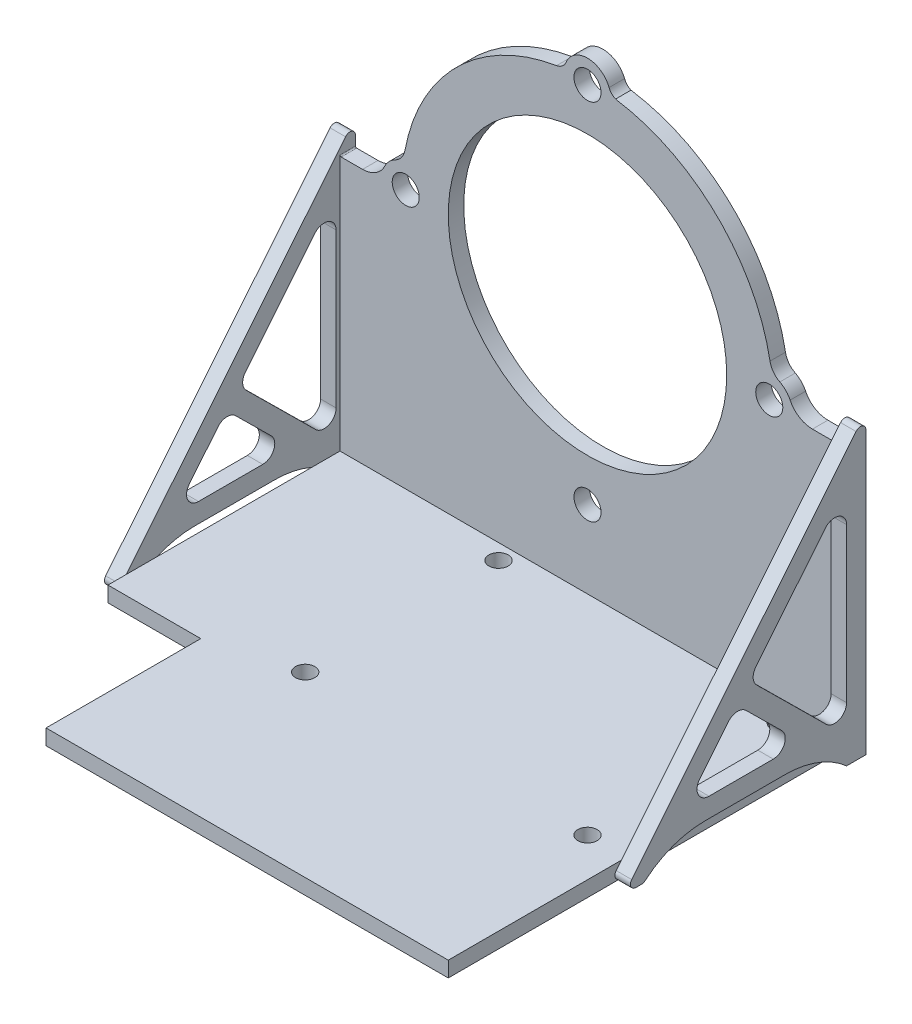
SolidWorks part; units mm, degrees
ref_plane "Front Plane" through (0, 0, 0) normal (0, 0, 1) x (1, 0, 0)
ref_plane "Top Plane" through (0, 0, 0) normal (0, 1, 0) x (1, 0, 0)
ref_plane "Right Plane" through (0, 0, 0) normal (1, 0, 0) x (0, 0, -1)
sketch "Sketch2" plane through (0, 0, 0) normal (0, 1, 0) x (1, 0, 0)
  line L0 (0, 0) -> (0, -101.6)
  line L1 (0, -101.6) -> (38.1, -101.6)
  line L2 (38.1, -101.6) -> (38.1, -165.1)
  line L3 (38.1, -165.1) -> (203.2, -165.1)
  line L4 (203.2, -165.1) -> (203.2, 0)
  line L5 (203.2, 0) -> (0, 0)
  dimension "D1" = 165.1
  dimension "D2" = 165.1
  dimension "D3" = 63.5
  dimension "D4" = 38.1
extrude "Boss-Extrude1" add sketch "Sketch2" along normal blind 6.35
sketch "Sketch3" plane through (0, 0, 0) normal (0, 0, 1) x (1, 0, 0)
  line L0 (203.2, 6.35) -> (203.2, 196.85)
  line L1 (203.2, 196.85) -> (0, 196.85)
  line L2 (0, 196.85) -> (0, 6.35)
  line L3 (0, 6.35) -> (203.2, 6.35)
  dimension "D1" = 190.5
extrude "Boss-Extrude2" add sketch "Sketch3" along normal blind 6.35
sketch "Sketch4" plane through (0, 0, 6.35) normal (0, 0, 1) x (1, 0, 0)
  line L0 (0, 6.35) -> (101.6, 6.35) construction
  line L1 (38.1, 6.35) -> (203.2, 6.35) construction
  line L2 (101.6, 6.35) -> (101.6, 112.7125) construction
  circle A0 centre (101.6, 112.7125) radius 57.15
  dimension "D3" = 114.3
  dimension "D1" = 101.6
  dimension "D2" = 106.3625
extrude "Cut-Extrude1" cut sketch "Sketch4" against normal blind 6.35
sketch "Sketch5" plane through (0, 0, 0) normal (0, 0, -1) x (-1, 0, 0)
  line L0 (0, 6.35) -> (-203.2, 6.35) construction
  line L1 (-101.6, 6.35) -> (-101.6, 38.1) construction
  circle A0 centre (-101.6, 38.1) radius 5.5563
  circle A1 centre (-101.6, 112.7125) radius 74.6125 construction
  circle A2 centre (-101.6, 187.325) radius 5.5563
  circle A3 centre (-26.9875, 112.7125) radius 5.5562
  circle A4 centre (-176.2125, 112.7125) radius 5.5563
  dimension "D2" = 11.1125
  dimension "D1" = 31.75
extrude "Cut-Extrude2" cut sketch "Sketch5" against normal blind 6.35
sketch "Sketch6" plane through (0, 0, 0) normal (0, 0, -1) x (-1, 0, 0)
  line L0 (-44.45, 112.7125) -> (-25.4, 112.7125) construction
  line L1 (0, 0) -> (0, 111.125) construction
  line L2 (0, 196.85) -> (0, 0) construction
  line L3 (0, 111.125) -> (-203.2, 111.125) construction
  line L4 (-203.2, 196.85) -> (-203.2, 0) construction
  line L5 (0, 111.125) -> (-9.2671, 111.125)
  line L6 (-88.3893, 190.8124) -> (-114.449, 190.8124) construction
  line L7 (-7.9098, 126.5898) -> (-186.0002, 126.5898) construction
  line L8 (-20.9502, 121.1931) -> (-193.0529, 121.1931) construction
  line L9 (-203.2, 111.125) -> (-193.9329, 111.125)
  line L10 (-203.2, 111.125) -> (-224.6051, 111.125)
  line L11 (-224.6051, 111.125) -> (-224.6051, 212.9952)
  line L12 (-224.6051, 212.9952) -> (24.4438, 212.9952)
  line L13 (24.4438, 212.9952) -> (24.4438, 111.125)
  line L14 (24.4438, 111.125) -> (0, 111.125)
  circle A0 centre (-101.6, 112.7125) radius 76.2 construction
  circle A1 centre (-101.6, 112.7125) radius 57.15 construction
  circle A2 centre (-101.6, 187.325) radius 9.525 construction
  circle A3 centre (-26.9875, 112.7125) radius 9.525 construction
  circle A4 centre (-176.2125, 112.7125) radius 9.525 construction
  arc A5 (-9.2671, 111.125) -> (-18.4131, 116.8605) centre (-9.2671, 121.285) cw
  arc A6 (-18.4131, 116.8605) -> (-22.651, 121.1931) centre (-26.9875, 112.7125) ccw
  arc A7 (-22.651, 121.1931) -> (-26.6743, 126.5898) centre (-19.1817, 127.9775) cw
  arc A8 (-26.6743, 126.5898) -> (-88.9325, 187.8522) centre (-101.6, 112.7125) ccw
  arc A9 (-88.9325, 187.8522) -> (-92.7364, 190.8124) centre (-88.088, 192.8615) cw
  arc A10 (-92.7364, 190.8124) -> (-110.4636, 190.8124) centre (-101.6, 187.325) ccw
  arc A11 (-110.4636, 190.8124) -> (-113.1099, 188.0382) centre (-115.1908, 192.6724) cw
  arc A12 (-113.1099, 188.0382) -> (-176.5257, 126.5898) centre (-101.6, 112.7125) ccw
  arc A13 (-176.5257, 126.5898) -> (-180.549, 121.1931) centre (-184.0183, 127.9775) cw
  arc A14 (-193.9329, 111.125) -> (-184.7869, 116.8605) centre (-193.9329, 121.285) ccw
  arc A15 (-184.7869, 116.8605) -> (-180.549, 121.1931) centre (-176.2125, 112.7125) cw
  point P49 (0, 0)
  point P53 (0, 0)
  dimension "D1" = 19.05
  dimension "D2" = 19.05
  dimension "D7" = 5.08
  dimension "D8" = 2.6463
  dimension "D10" = 10.16
  dimension "D9" = 7.62
  dimension "D11" = 5.08
  dimension "D12" = 7.62
  dimension "D13" = 10.16
  dimension "D3" = 111.125
  dimension "D5" = 249.0489
  dimension "D6" = 21.4051
extrude "Cut-Extrude3" cut sketch "Sketch6" against normal blind 6.35
sketch "Sketch7" plane through (0, 6.35, 0) normal (0, 1, 0) x (1, 0, 0)
  line L0 (203.2, -92.075) -> (187.325, -92.075) construction
  line L1 (203.2, -165.1) -> (203.2, -6.35) construction
  line L2 (0, -6.35) -> (203.2, -6.35) construction
  line L3 (187.325, -92.075) -> (187.325, -6.35) construction
  line L4 (187.325, -12.7) -> (203.2, -12.7) construction
  line L5 (71.4375, -12.7) -> (71.4375, -92.075) construction
  circle A0 centre (187.325, -92.075) radius 3.9687
  circle A1 centre (187.325, -12.7) radius 3.9687
  circle A2 centre (71.4375, -12.7) radius 3.9688
  circle A3 centre (71.4375, -92.075) radius 3.9687
  dimension "D3" = 7.9375
  dimension "D1" = 15.875
  dimension "D2" = 85.725
  dimension "D4" = 79.375
  dimension "D5" = 115.8875
extrude "Cut-Extrude4" cut sketch "Sketch7" against normal blind 6.35
sketch "Sketch8" plane through (0, 0, 0) normal (1, 0, 0) x (0, 0, -1)
  line L0 (0, 0) -> (-99.2187, 0)
  line L1 (-165.1, 0) -> (0, 0) construction
  line L2 (-99.2187, 0) -> (0, 121.92)
  line L3 (0, 111.125) -> (0, 0) construction
  line L4 (0, 121.92) -> (0, 0)
  dimension "D1" = 121.92
  dimension "D2" = 99.2188
extrude "Boss-Extrude3" add sketch "Sketch8" against normal blind 6.35
sketch "Sketch10" plane through (203.2, 0, 0) normal (1, 0, 0) x (0, 0, -1)
  line L0 (-99.2188, 0) -> (0, 0)
  line L1 (0, 0) -> (0, 121.92)
  line L2 (0, 111.125) -> (0, 0) construction
  line L3 (0, 121.92) -> (-99.2188, 0)
  dimension "D1" = 121.92
  dimension "D2" = 99.2188
extrude "Boss-Extrude4" add sketch "Sketch10" along normal blind 6.35
sketch "Sketch11" plane through (209.55, 0, 0) normal (1, 0, 0) x (0, 0, -1)
  line L1 (-7.9375, 0) -> (-91.2813, 0)
  line L2 (-99.2188, 0) -> (0, 0) construction
  line L3 (-66.0805, 9.525) -> (-33.1383, 9.525)
  arc A0 (-91.2813, 0) -> (-66.0805, 9.525) centre (-66.0805, -28.575) cw
  arc A1 (-33.1383, 9.525) -> (-7.9375, 0) centre (-33.1383, -28.575) cw
  dimension "D4" = 38.1
  dimension "D5" = 38.1
  dimension "D1" = 7.9375
  dimension "D2" = 7.9375
  dimension "D3" = 9.525
extrude "Cut-Extrude5" cut sketch "Sketch11" against normal up to surface (6.35 mm away) contours L1 A0 L3 A1 up to face at (203.2, 3.175, 130.8675)
sketch "Sketch12" plane through (-6.35, 0, 0) normal (-1, 0, 0) x (0, 0, 1)
  line L0 (91.2813, 0) -> (7.9375, 0)
  line L1 (33.1383, 9.525) -> (66.0805, 9.525)
  line L2 (99.2187, 0) -> (0, 0) construction
  arc A0 (7.9375, 0) -> (33.1383, 9.525) centre (33.1383, -28.575) cw
  arc A1 (66.0805, 9.525) -> (91.2813, 0) centre (66.0805, -28.575) cw
  dimension "D1" = 38.1
  dimension "D2" = 38.1
  dimension "D3" = 7.9375
  dimension "D4" = 9.525
  dimension "D5" = 7.9375
extrude "Cut-Extrude6" cut sketch "Sketch12" against normal up to surface (6.35 mm away) up to face at (0, 3.175, 99.1175)
sketch "Sketch13" plane through (209.55, 0, 0) normal (1, 0, 0) x (0, 0, -1)
  line L0 (-7.9375, 99.5912) -> (-7.9375, 10.6912)
  line L1 (0, 0) -> (0, 121.92) construction
  line L2 (-7.9375, 99.5912) -> (-48.0187, 50.3393)
  line L3 (0, 121.92) -> (-99.2188, 0) construction
  line L4 (-48.0187, 50.3393) -> (-7.9375, 10.6912)
  line L5 (-24.1458, 79.6745) -> (-79.515, 11.6368) construction
  line L6 (0, 121.92) -> (-11.0085, 121.92) construction
  line L7 (-89.376, 17.4625) -> (3.2132, 17.4625) construction
  line L8 (-66.0805, 9.525) -> (-33.1383, 9.525) construction
  line L9 (-53.8667, 44.9593) -> (-22.964, 14.3904) construction
  line L10 (-53.0525, 44.1538) -> (-26.0696, 17.4625)
  line L11 (-53.0525, 44.1538) -> (-74.774, 17.4625)
  line L12 (-26.0696, 17.4625) -> (-74.774, 17.4625)
  point P10 (-48.0187, 50.3393)
  point P18 (-7.9375, 10.6912)
  point P21 (-7.9375, 99.5912)
  dimension "D5" = 7.9375
  dimension "D1" = 7.9375
  dimension "D2" = 7.9375
  dimension "D3" = 88.9
  dimension "D4" = 63.5
  dimension "D6" = 7.9375
extrude "Cut-Extrude7" cut sketch "Sketch13" against normal through all contours L11 L12 L10 | L0 L4 L2
fillet "Fillet1" radius 4.92 12 edges at (206.375, 99.5912, 7.9375) (206.375, 17.4625, 26.0696) (206.375, 17.4625, 74.774) (206.375, 44.1538, 53.0525) (206.375, 50.3393, 48.0187) (206.375, 10.6912, 7.9375) (-3.175, 17.4625, 26.0696) (-3.175, 17.4625, 74.774) (-3.175, 44.1538, 53.0525) (-3.175, 50.3393, 48.0187) (-3.175, 10.6912, 7.9375) (-3.175, 99.5912, 7.9375)
fillet "Fillet4" radius 2.286 6 edges at (-3.175, 121.92, 0) (206.375, 121.92, 0) (206.375, 0, 91.2812) (206.375, 0, 99.2187) (-3.175, 0, 91.2813) (-3.175, 0, 99.2187)
fillet "Fillet6" radius 0.508 1 edges at (0, 111.125, 3.175)
